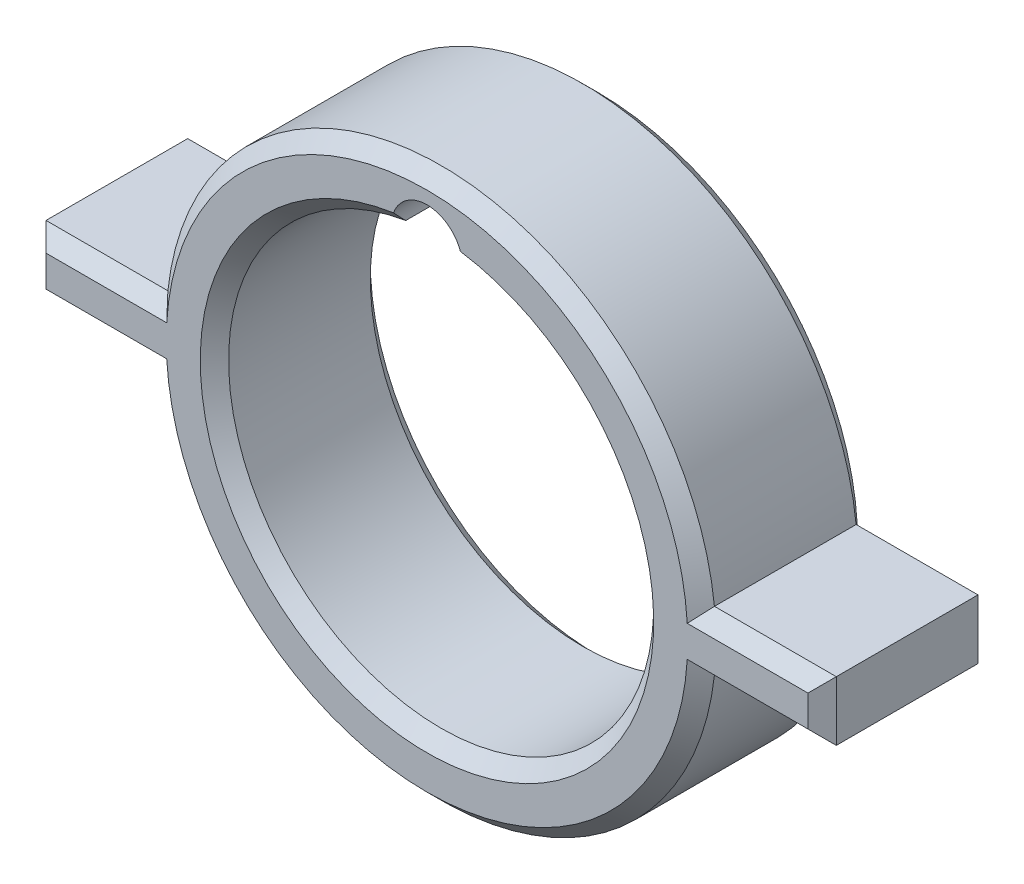
SolidWorks part; units mm, degrees
material "PLA"
ref_plane "Front Plane" through (0, 0, 0) normal (0, 0, 1) x (1, 0, 0)
ref_plane "Top Plane" through (0, 0, 0) normal (0, 1, 0) x (1, 0, 0)
ref_plane "Right Plane" through (0, 0, 0) normal (1, 0, 0) x (0, 0, -1)
sketch "Sketch1" plane through (0, 0, 0) normal (0, 0, 1) x (1, 0, 0)
  line L6 (9.643, -1.05) -> (13.943, -1.05)
  line L7 (13.943, -1.05) -> (13.943, 1.05)
  line L8 (13.943, 1.05) -> (9.643, 1.05)
  line L9 (-13.943, 1.05) -> (-13.943, -1.05)
  line L10 (-9.643, 1.05) -> (-13.943, 1.05)
  line L11 (-13.943, -1.05) -> (-9.643, -1.05)
  line L12 (0, 0) -> (16.0081, 0) construction
  line L13 (0, 0) -> (0, -4.3408) construction
  arc A4 (9.643, 1.05) -> (-9.643, 1.05) centre (0, 0) ccw
  arc A5 (-9.643, -1.05) -> (9.643, -1.05) centre (0, 0) ccw
  circle A6 centre (0, 0) radius 7.5
  dimension "D1" = 9.7
  dimension "D4" = 15
  dimension "D2" = 2.1
  dimension "D3" = 4.3
extrude "Boss-Extrude1" add sketch "Sketch1" along normal blind 6
chamfer "Chamfer1" distance 0.5 angle 45 18 edges at (7.5, 0, 0) (-13.943, 0, 0) (-11.793, -1.05, 0) (0, -9.7, 0) (11.793, -1.05, 0) (13.943, 0, 0) (11.793, 1.05, 0) (0, 9.7, 0) (-11.793, 1.05, 0) (7.5, 0, 6) (0, 9.7, 6) (11.793, 1.05, 6) (13.943, 0, 6) (11.793, -1.05, 6) (0, -9.7, 6) (-11.793, -1.05, 6) (-13.943, 0, 6) (-11.793, 1.05, 6)
sketch "Sketch2" plane through (0, 0, 0) normal (0, 0, -1) x (-1, 0, 0)
  line L0 (0, 0) -> (0, 7.5) construction
  circle A0 centre (0, 0) radius 7.5 construction
  circle A1 centre (0, 7.5) radius 1.25
  dimension "D1" = 2.5
extrude "Cut-Extrude1" cut sketch "Sketch2" against normal blind 10
